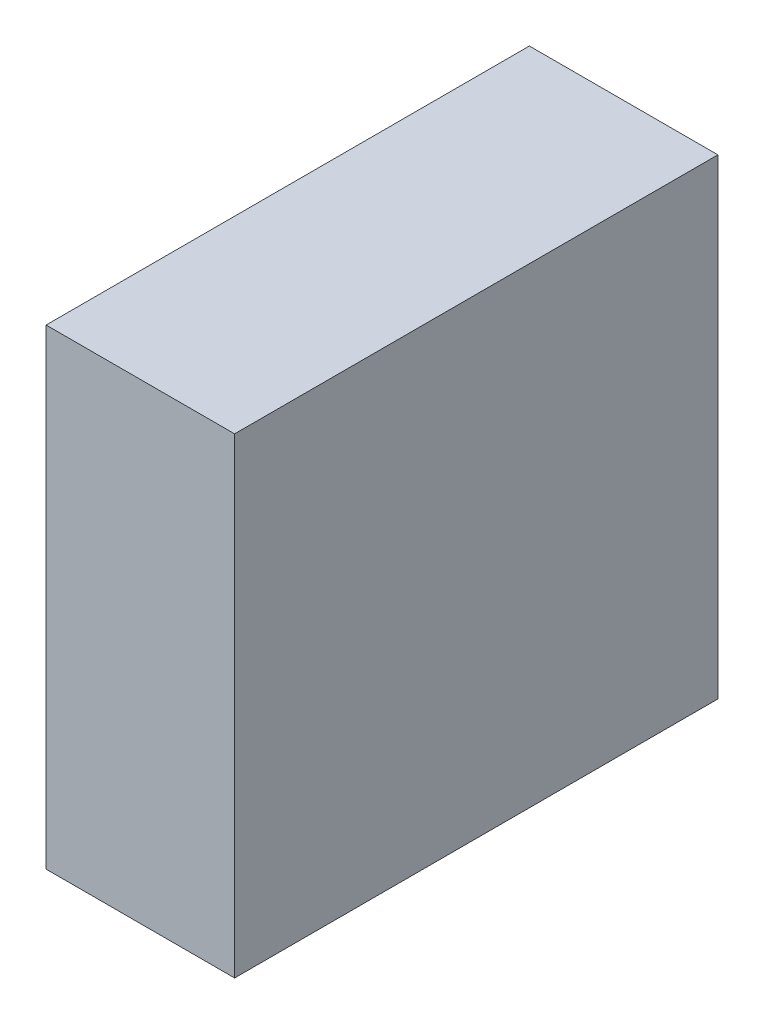
SolidWorks part; units mm, degrees
material "6061 Alloy"
ref_plane "Front Plane" through (0, 0, 0) normal (0, 0, 1) x (1, 0, 0)
ref_plane "Top Plane" through (0, 0, 0) normal (0, 1, 0) x (1, 0, 0)
ref_plane "Right Plane" through (0, 0, 0) normal (1, 0, 0) x (0, 0, -1)
sketch "Sketch1" plane through (0, 0, 0) normal (0, 0, 1) x (1, 0, 0)
  line L1 (-12.7, 31.75) -> (12.7, 31.75)
  line L2 (-12.7, 31.75) -> (-12.7, -31.75)
  line L3 (-12.7, -31.75) -> (12.7, -31.75)
  line L4 (12.7, 31.75) -> (12.7, -31.75)
  line L5 (-12.7, 31.75) -> (12.7, -31.75) construction
  line L6 (-12.7, -31.75) -> (12.7, 31.75) construction
  point P0 (0, 0)
  dimension "D1" = 63.5
  dimension "D2" = 25.4
extrude "Boss-Extrude1" add sketch "Sketch1" along normal blind 65.12
